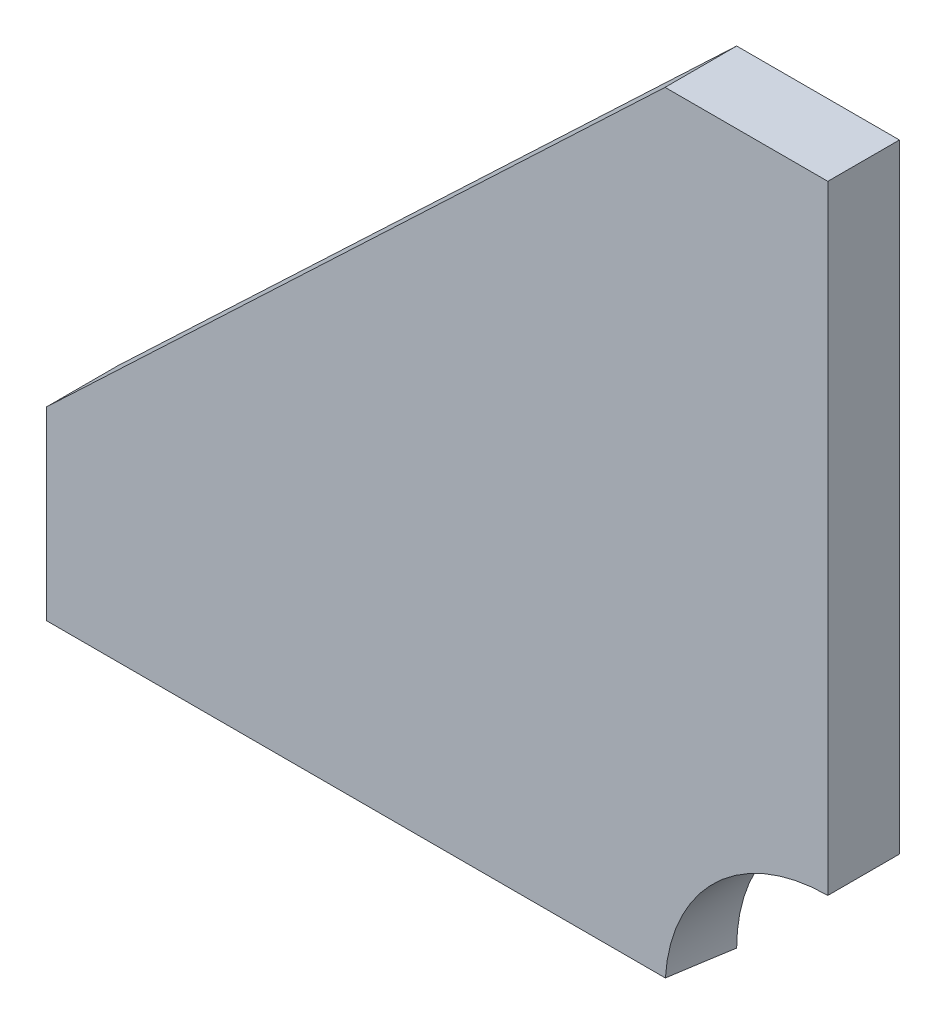
SolidWorks part; units mm, degrees
material "1.0116 (S235J2G3)"
ref_plane "Front Plane" through (0, 0, 0) normal (0, 0, 1) x (1, 0, 0)
ref_plane "Top Plane" through (0, 0, 0) normal (0, 1, 0) x (1, 0, 0)
ref_plane "Right Plane" through (0, 0, 0) normal (1, 0, 0) x (0, 0, -1)
sketch "Sketch1" plane through (0, 0, 0) normal (0, 0, 1) x (1, 0, 0)
  line L0 (0, 0) -> (25, 0)
  line L1 (25, 0) -> (25, -120)
  line L2 (0, 0) -> (-95, -90)
  line L3 (-95, -90) -> (-95, -120)
  line L4 (-95, -120) -> (25, -120)
  circle A0 centre (25, -120) radius 25
  dimension "D5" = 50
  dimension "D1" = 25
  dimension "D2" = 120
  dimension "D3" = 120
  dimension "D4" = 30
extrude "Boss-Extrude1" add sketch "Sketch1" along normal blind 11 contours A0 L1 L0 L2 L3 L4
sketch "Sketch2" plane through (-95, 0, 0) normal (-1, 0, 0) x (0, 0, 1)
  line L0 (0, -120) -> (11, -120)
  line L1 (11, -120) -> (11, -118.4541)
  line L2 (11, -90) -> (11, -120) construction
  line L3 (11, -118.4541) -> (0, -120)
  dimension "D1" = 8
extrude "Cut-Extrude1" cut sketch "Sketch2" against normal blind 116
